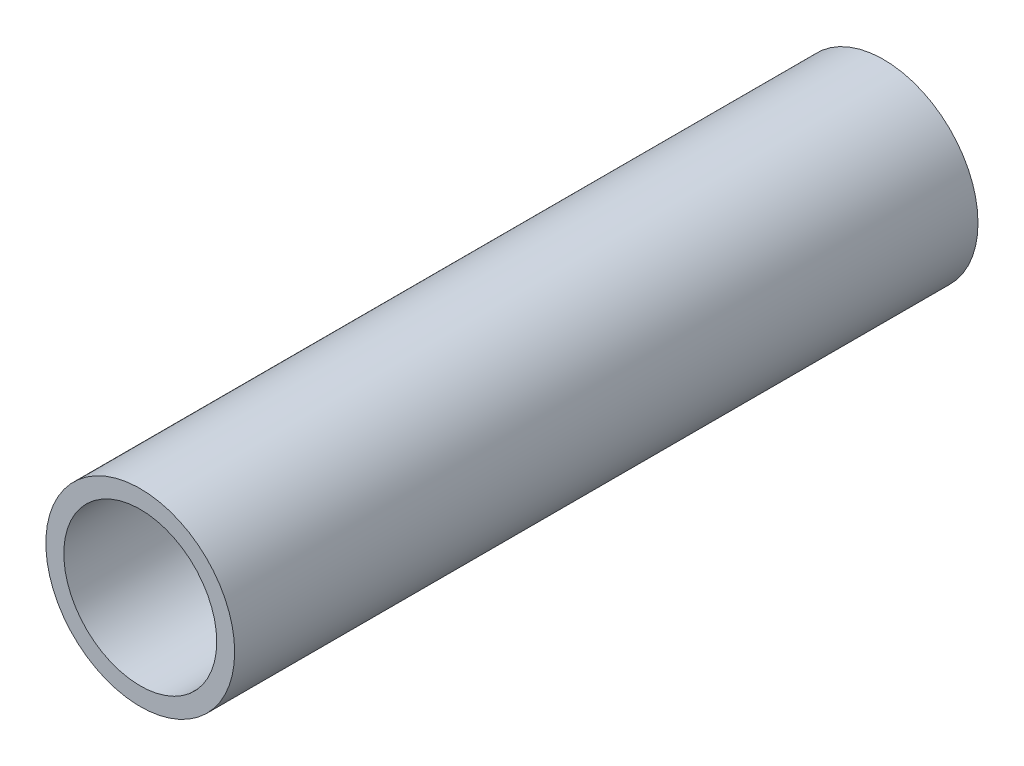
SolidWorks part; units mm, degrees
material "AISI 4340 Steel, annealed"
ref_plane "Front Plane" through (0, 0, 0) normal (0, 0, 1) x (1, 0, 0)
ref_plane "Top Plane" through (0, 0, 0) normal (0, 1, 0) x (1, 0, 0)
ref_plane "Right Plane" through (0, 0, 0) normal (1, 0, 0) x (0, 0, -1)
sketch "Sketch3" plane through (0, 0, 0) normal (0, 0, 1) x (1, 0, 0)
  circle A0 centre (0, 0) radius 12.7
  circle A1 centre (0, 0) radius 10.287
  dimension "D1" = 25.4
  dimension "D2" = 2.413
extrude "Boss-Extrude1" add sketch "Sketch3" along normal blind 100
ref_plane "Plane1" through (0, 0, 50) normal (0, 0, -1) x (-1, 0, 0)
